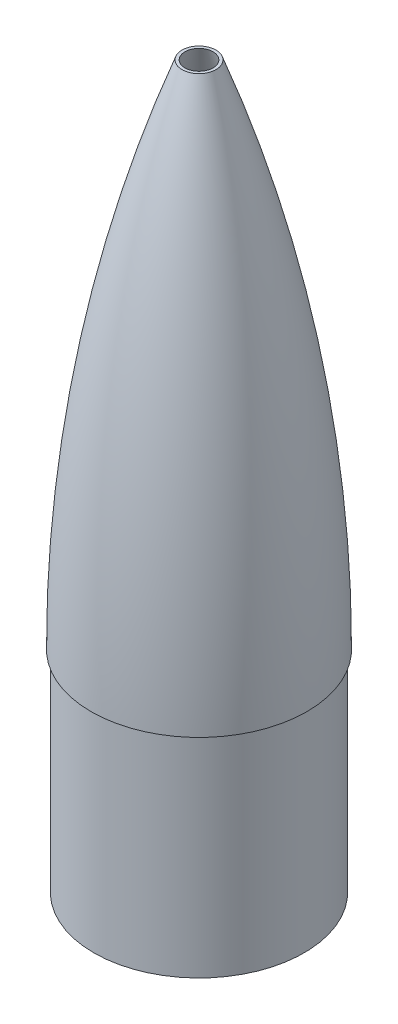
SolidWorks part; units mm, degrees
other "Markup1"
sketch "Sketch4" plane through (78.16, -154.2442, 78.16) normal (0.9651, -0.1718, 0.1975) x (-0.1686, -0.9851, -0.0334)
material "Thornel Mat VMA"
ref_plane "Front Plane" through (0, 0, 0) normal (0, 0, 1) x (1, 0, 0)
ref_plane "Top Plane" through (0, 0, 0) normal (0, 1, 0) x (1, 0, 0)
ref_plane "Right Plane" through (0, 0, 0) normal (1, 0, 0) x (0, 0, -1)
sketch "Sketch1" plane through (0, 0, 0) normal (0, 0, 1) x (1, 0, 0)
  line L3 (0, 0) -> (0, 398.8705) construction
  line L6 (0, 400) -> (0, 401.8534)
  line L8 (78.2, 0) -> (76.2, 0)
  line L9 (0, 400) -> (0, 396.4892)
  line L10 (76.2, 0) -> (-993.4203, 0) construction
  line L11 (0, 411.0234) -> (0, 614.1078) construction
  arc A0 (76.2, 0) -> (0, 396.4892) centre (-993.4203, 0) ccw
  arc A1 (78.2, 0) -> (0, 401.8534) centre (-993.4203, 0) ccw
  circle A2 centre (-993.4203, 0) radius 1069.6203 construction
  circle A3 centre (-993.4203, 0) radius 1071.6203 construction
  point P11 (0, 400)
  dimension "D1" = 400
  dimension "D2" = 3.5108
  dimension "D3" = 2
  dimension "D4" = 76.2
revolve "Revolve3" add sketch "Sketch1" angle 360 about L6
sketch "Sketch2" plane through (0, 0, 0) normal (0, 1, 0) x (1, 0, 0)
  circle A3 centre (0, 0) radius 76.2 construction
  circle A4 centre (0, 0) radius 76.2
  circle A5 centre (0, 0) radius 74.2
  dimension "D1" = 2
extrude "Boss-Extrude1" add sketch "Sketch2" against normal blind 152.4 and the other way blind 10
ref_plane "Plane2" through (0, 400, 0) normal (0, -1, 0) x (-1, 0, 0)
ref_plane "Plane4" through (0, 370, 0) normal (0, -1, 0) x (-1, 0, 0)
sketch "Sketch6" plane through (0, 370, 0) normal (0, -1, 0) x (-1, 0, 0)
  circle A0 centre (0, 0) radius 45.0274
extrude "Cut-Extrude1" cut sketch "Sketch6" against normal blind 40
ref_plane "Plane3" through (0, -6.4, 0) normal (0, -1, 0) x (-1, 0, 0)
sketch "Sketch5" plane through (0, -6.4, 0) normal (0, -1, 0) x (-1, 0, 0)
  circle A0 centre (0, 0) radius 74.2
  circle A1 centre (0, 0) radius 74.2
